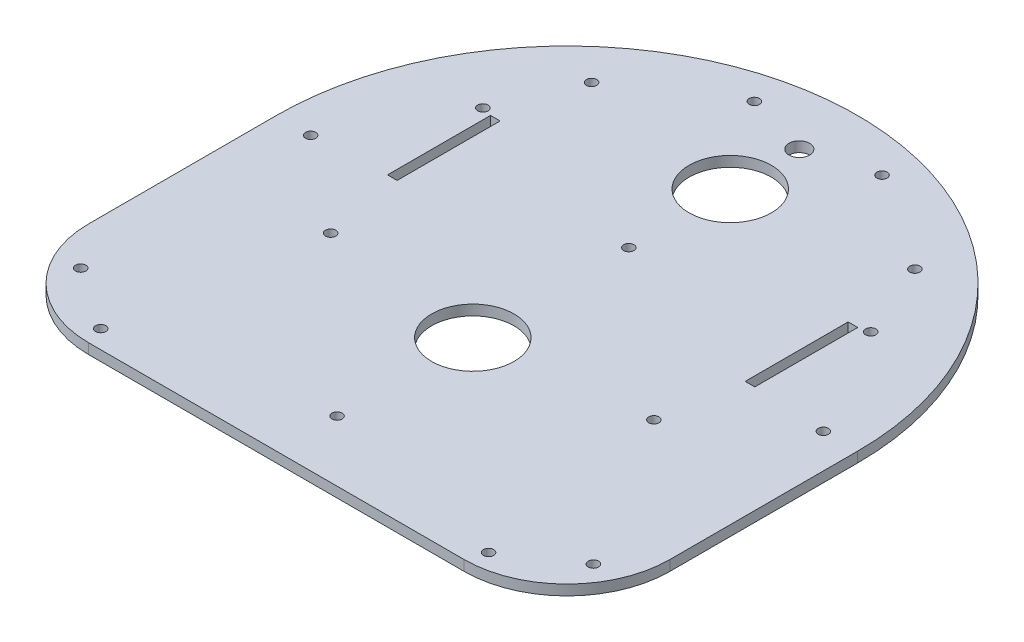
SolidWorks part; units mm, degrees
ref_plane "Front Plane" through (0, 0, 0) normal (0, 0, 1) x (1, 0, 0)
ref_plane "Top Plane" through (0, 0, 0) normal (0, 1, 0) x (1, 0, 0)
ref_plane "Right Plane" through (0, 0, 0) normal (1, 0, 0) x (0, 0, -1)
sketch "Sketch1" plane through (0, 0, 0) normal (0, 1, 0) x (1, 0, 0)
  line L85 (-15.8131, -40.9116) -> (-15.8131, -10.9116)
  line L86 (-117.2131, -10.9116) -> (-120.0131, -10.9116)
  line L87 (-121.1964, -126.8083) -> (-11.8298, -126.8083)
  line L90 (-13.0131, -40.9116) -> (-15.8131, -40.9116)
  line L91 (-13.0131, -10.9116) -> (-13.0131, -40.9116)
  line L92 (-15.8131, -10.9116) -> (-13.0131, -10.9116)
  line L93 (-120.0131, -10.9116) -> (-120.0131, -40.9116)
  line L94 (-120.0131, -40.9116) -> (-117.2131, -40.9116)
  line L95 (-117.2131, -40.9116) -> (-117.2131, -10.9116)
  line L96 (-151.1964, -42.125) -> (-151.1964, -96.8083)
  line L97 (18.1702, -96.8083) -> (18.1702, -42.125)
  circle A87 centre (-19.4171, 12.134) radius 1.5
  circle A91 centre (-113.6092, 12.134) radius 1.5
  circle A96 centre (8.1702, -42.125) radius 1.5
  circle A97 centre (-141.1964, -42.125) radius 1.5
  circle A98 centre (-66.5131, 5.4353) radius 12
  circle A99 centre (-66.5131, 25.5584) radius 3
  circle A100 centre (-66.5131, -69.5647) radius 12
  circle A104 centre (-123.0131, -10.1384) radius 1.5
  circle A110 centre (-10.0131, -10.1384) radius 1.5
  circle A111 centre (-10.0131, -121.4784) radius 1.5
  circle A112 centre (-123.0131, -121.4784) radius 1.5
  circle A128 centre (-66.5131, -109.125) radius 1.5
  circle A129 centre (-66.5131, -24.125) radius 1.5
  circle A132 centre (-141.1964, -109.125) radius 1.5
  circle A133 centre (8.1702, -109.125) radius 1.5
  arc A140 (-151.1964, -96.8083) -> (-121.1964, -126.8083) centre (-121.1964, -96.8083) ccw
  arc A141 (18.1702, -42.125) -> (-151.1964, -42.125) centre (-66.5131, -42.125) ccw
  arc A142 (-11.8298, -126.8083) -> (18.1702, -96.8083) centre (-11.8298, -96.8083) ccw
  circle A147 centre (-19.4171, 12.134) radius 1.5
  circle A148 centre (-19.4171, -63.9123) radius 1.5
  circle A149 centre (-113.6092, -63.9123) radius 1.5
  circle A150 centre (-113.6092, 12.134) radius 1.5
  circle A151 centre (-85.1092, 31.0584) radius 1.5
  circle A152 centre (-47.9171, 31.0584) radius 1.5
  point P2 (0, 0)
extrude "Boss-Extrude4" add sketch "Sketch1" along normal blind 3
